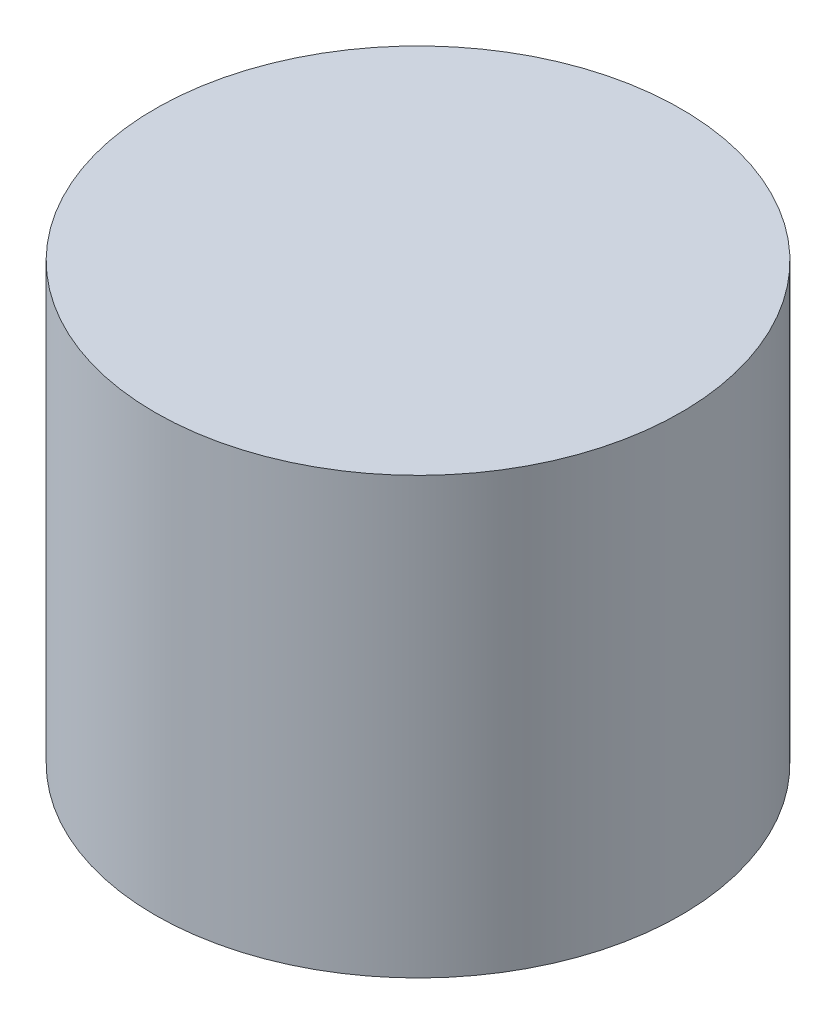
SolidWorks part; units mm, degrees
ref_plane "前视基准面" through (0, 0, 0) normal (0, 0, 1) x (1, 0, 0)
ref_plane "上视基准面" through (0, 0, 0) normal (0, 1, 0) x (1, 0, 0)
ref_plane "右视基准面" through (0, 0, 0) normal (1, 0, 0) x (0, 0, -1)
sketch "草图1" plane through (0, 0, 0) normal (0, 1, 0) x (1, 0, 0)
  circle A0 centre (0, 0) radius 145
  dimension "D1" = 290
extrude "凸台-拉伸1" add sketch "草图1" along normal blind 240
